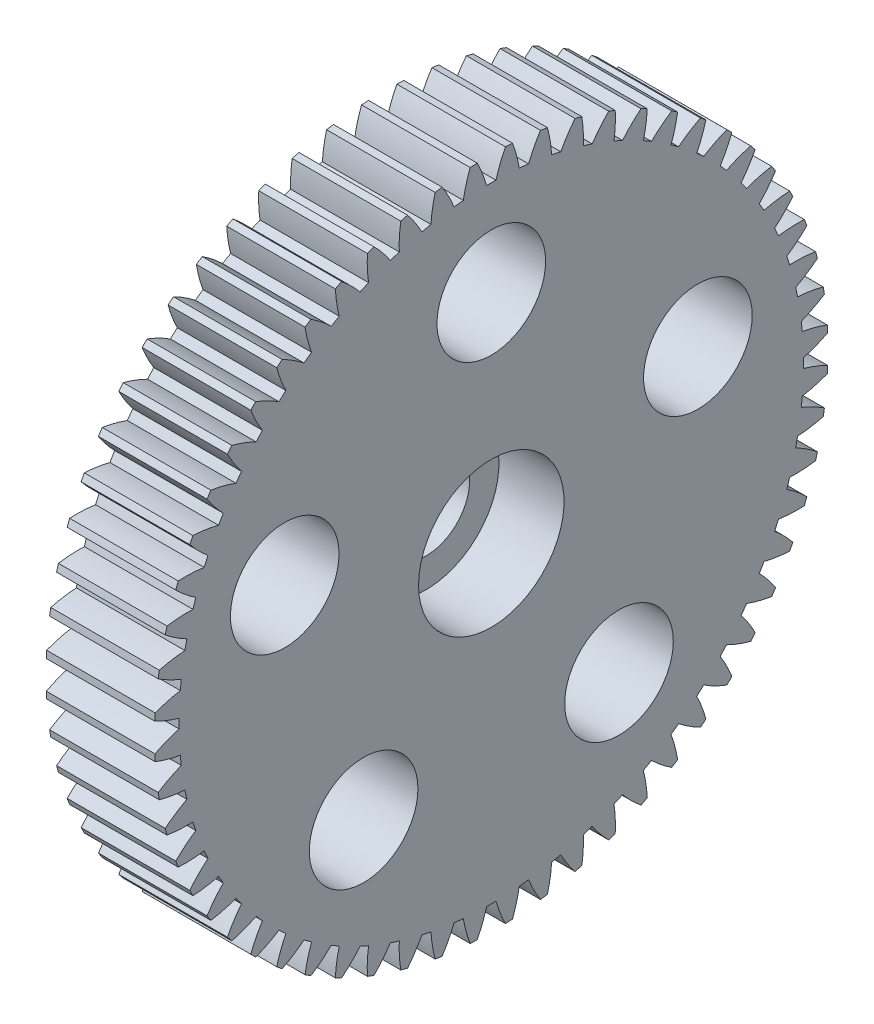
SolidWorks part; units mm, degrees
ref_plane "Plane1" through (0, 0, 0) normal (0, 0, 1) x (1, 0, 0)
ref_plane "Plane2" through (0, 0, 0) normal (0, 1, 0) x (1, 0, 0)
ref_plane "Plane3" through (0, 0, 0) normal (1, 0, 0) x (0, 0, -1)
sketch "HoldingSke" plane through (0, 0, 0) normal (0, 1, 0) x (1, 0, 0)
  line L0 (0, 0) -> (0.5, -0.866)
  line L1 (-15, 0) -> (100, 0) construction
  line L2 (0, 0) -> (-2.1039, 2.3779)
  line L3 (0, 0) -> (-11.863, 4.5341)
  line L4 (0, 0) -> (4.318, 7.479)
  line L5 (0, 0) -> (-46.8476, -17.4728)
  line L6 (0, 0) -> (-4.1448, -2.7965)
  line L7 (-2.1039, 2.3779) -> (8.6586, 51.2059)
  line L8 (-76.2, 54.61) -> (-75.7, 54.61)
  line L9 (-71.009, 38.7566) -> (-53.1078, 45.2721)
  line L10 (-76.2, 71.12) -> (104.1128, 71.12)
  line L11 (0, 0) -> (-5, 0)
  line L12 (-76.2, 101.6) -> (-76.162, 101.6)
  line L13 (24.9733, 27.94) -> (52.9518, 28.4284)
  line L14 (24.9733, 27.94) -> (24.9743, 27.94)
  line L15 (24.9733, 27.94) -> (100.4006, 29.5858)
  line L16 (-63.627, -1) -> (-12.827, -1)
  circle A0 centre (0, 0) radius 1.5
  circle A1 centre (0, 0) radius 28.749
  circle A2 centre (0, 0) radius 37.5
  circle A3 centre (0, 0) radius 1.5
  dimension "MHD" = 57.498
  dimension "Hub_dia" = 75
  dimension "Bore" = 3
  dimension "MBD" = 3
  dimension "Num_teeth" = 60
  dimension "Pitch" = 1
  dimension "Overall_len" = 50
  dimension "Show_teeth" = 60
  dimension "Thickness" = 5
  dimension "OAL" = 50.0001
  dimension "T_dim" = 0.5
  dimension "Ap" = 20
  dimension "H" = 19.05
  dimension "Pitch_radius" = 180.3128
  dimension "Width" = 5
  dimension "Backlash" = 0.038
  dimension "Addendum_fac" = 1
  dimension "Dedendum_fac" = 1.25
  dimension "Clearance_fac" = 0.25
  dimension "Dedendum_add" = 0.001
  dimension "Module" = 1
sketch "BasProSke" plane through (0, 0, 0) normal (0, 1, 0) x (1, 0, 0)
  line L0 (-10, 0) -> (60, 0) construction
  line L1 (0, 0) -> (0, 31)
  line L2 (0, 0) -> (10, 0)
  line L3 (10, 0) -> (10, 31)
  line L4 (10, 31) -> (0, 31)
  dimension "Thickness" = 10
  dimension "Diameter" = 62
revolve "Base-Revolve" add sketch "BasProSke" angle 360 about L0
sketch "TooCutSke" plane through (0, 0, 0) normal (1, 0, 0) x (0, 0, -1)
  line L1 (0, 0) -> (0, 107) construction
  line L2 (0, 0) -> (-0.8518, 29.9879) construction
  line L3 (0, 0) -> (-3.1393, 59.9006) construction
  line L4 (-0.8518, 29.9879) -> (-1.5696, 29.9503) construction
  arc A0 (0.4302, 28.7458) -> (-0.4302, 28.7458) centre (0, 0) ccw
  arc A1 (1.3127, 30.9976) -> (-1.3127, 30.9976) centre (0, 0) ccw
  circle A2 centre (0, 0) radius 30 construction
  circle A3 centre (0, 0) radius 28.1908 construction
  arc A4 (-0.4302, 28.7458) -> (-1.3127, 30.9976) centre (-11.9871, 25.5153) ccw
  arc A5 (1.3127, 30.9976) -> (0.4302, 28.7458) centre (11.9871, 25.5153) ccw
  dimension "Root_dia" = 57.498
  dimension "Overcut_dia" = 62.0508
  dimension "Pitch_dia" = 60
  dimension "Base_dia" = 56.3816
  dimension "Flank_rad" = 12
  dimension "Half_ang" = 3
  dimension "Half_CT" = 0.7188
extrude "ToothCut" cut sketch "TooCutSke" along normal through all
fillet "Breaks" [suppressed] radius 0.02
fillet "RootFillets" [suppressed] radius 0.251
pattern_circular "TeethCuts" count 60 over 360 about axis through (0, 0, 0) along (1, 0, 0) of "ToothCut", "RootFillets", "Breaks"
sketch "HubNeaOneSke" plane through (0, 0, 0) normal (-1, 0, 0) x (0, 0, 1)
  circle A0 centre (0, 0) radius 28.749
  dimension "Diameter" = 57.498
extrude "HubNearOne" [suppressed] add sketch "HubNeaOneSke" along normal blind 40.0001
sketch "HubNeaBotSke" plane through (0, 0, 0) normal (-1, 0, 0) x (0, 0, 1)
  circle A0 centre (0, 0) radius 28.749
  dimension "Diameter" = 57.498
extrude "HubNearBoth" [suppressed] add sketch "HubNeaBotSke" along normal blind 20
ref_plane "FarPln" through (10, 0, 0) normal (1, 0, 0) x (0, 0, -1)
sketch "HubFarSke" plane through (10, 0, 0) normal (1, 0, 0) x (0, 0, -1)
  circle A0 centre (0, 0) radius 28.749
  dimension "Diameter" = 57.498
extrude "HubFar" [suppressed] add sketch "HubFarSke" along normal blind 20
sketch "BorSke" plane through (0, 0, 0) normal (1, 0, 0) x (0, 0, -1)
  circle A0 centre (0, 0) radius 6.7
  dimension "Diameter" = 13.4
extrude "Bore" cut sketch "BorSke" along normal mid plane 100.0001
sketch "KeySke" plane through (0, 0, 0) normal (1, 0, 0) x (0, 0, -1)
  line L0 (-0.6, 0) -> (-0.6, 2)
  line L1 (-0.6, 2) -> (0.6, 2)
  line L2 (0.6, 2) -> (0.6, 0)
  line L3 (0, 0) -> (0, 34) construction
  line L4 (-0.6, 0) -> (0.6, 0)
  dimension "Offset" = 2
  dimension "Width" = 1.2
extrude "Keyway" [suppressed] cut sketch "KeySke" along normal mid plane 100.0001
sketch "草图1" plane through (10, 0, 0) normal (1, 0, 0) x (0, 0, -1)
  circle A0 centre (0, 20) radius 5
  circle A1 centre (0, 0) radius 6.7 construction
  circle A2 centre (19.0211, 6.1803) radius 5
  circle A3 centre (11.7557, -16.1803) radius 5
  circle A4 centre (-11.7557, -16.1803) radius 5
  circle A5 centre (-19.0211, 6.1803) radius 5
  point P14 (0, 0)
  dimension "D1" = 10
  dimension "D2" = 20
  dimension "D3" = 5
extrude "切除-拉伸2" cut sketch "草图1" against normal blind 10
sketch "草图3" plane through (0, 0, 0) normal (-1, 0, 0) x (0, 0, 1)
  circle A0 centre (0, 0) radius 6.7
  circle A1 centre (0, 0) radius 4
  circle A2 centre (0, 0) radius 6.7 construction
  dimension "D1" = 8
extrude "凸台-拉伸2" add sketch "草图3" against normal blind 4
equation "' \"Module@HoldingSke\" = 6.35"
equation "' \"Num_teeth@HoldingSke\" = 12"
equation "' \"Ap@HoldingSke\" =  20"
equation "' \"Ap@HoldingSke\" = 20"
equation "' \"Width@HoldingSke\" = 0.5 * 25.4"
equation "' \"Hub_dia@HoldingSke\"= 1 * 25.4"
equation "' \"Hub_dia@HoldingSke\" = 1 * 25.4"
equation "' \"Overall_len@HoldingSke\" = 1.0 * 25.4"
equation "' \"Bore@HoldingSke\" = 0.75 * 25.4"
equation "' \"T_dim@HoldingSke\" = 0.1 * 25.4"
equation "' \"Width@KeySke\" = 0.25 * 25.4"
equation "' \"Show_teeth@HoldingSke\" = 13"
equation "' \"Backlash@HoldingSke\" = 0.009 * 25.4"
equation "' \"Addendum_fac@HoldingSke\" = 1.0"
equation "' \"Dedendum_fac@HoldingSke\" = 1.25"
equation "' \"Dedendum_add@HoldingSke\" = 0.00005 * 25.4"
equation "' \"Clearance_fac@HoldingSke\" = 0.25"
equation "\"Pitch@HoldingSke\" = 1 / \"Module@HoldingSke\""
equation "\"Overcut_dia@TooCutSke\" = (\"Num_teeth@HoldingSke\" + 2 * \"Addendum_fac@HoldingSke\") / \"Pitch@HoldingSke\" + 0.002 * 25.4"
equation "\"Pitch_dia@TooCutSke\" = \"Num_teeth@HoldingSke\" / \"Pitch@HoldingSke\""
equation "\"Base_dia@TooCutSke\" = \"Num_teeth@HoldingSke\" / \"Pitch@HoldingSke\" * cos((\"Ap@HoldingSke\"  * 3.14159265 / 180))"
equation "\"Root_dia@TooCutSke\" = (\"Num_teeth@HoldingSke\" + 2) / \"Pitch@HoldingSke\" - 2 * (\"Addendum_fac@HoldingSke\" + \"Dedendum_fac@HoldingSke\") / \"Pitch@HoldingSke\" - \"Dedendum_add@HoldingSke\" * 2"
equation "\"Half_ang@TooCutSke\" = 180 / \"Num_teeth@HoldingSke\""
equation "\"Half_CT@TooCutSke\" = \"Num_teeth@HoldingSke\" / \"Pitch@HoldingSke\" * sin((3.14159265 / 2 / \"Num_teeth@HoldingSke\")) / 2 - 7 * \"Backlash@HoldingSke\" / 4"
equation "\"Flank_rad@TooCutSke\" = \"Num_teeth@HoldingSke\" / \"Pitch@HoldingSke\" / 5"
equation "\"Radius@RootFillets\" = \"Clearance_fac@HoldingSke\" / \"Pitch@HoldingSke\" + \"Dedendum_add@HoldingSke\""
equation "\"Break_rad@Breaks\" = 0.02 / \"Pitch@HoldingSke\""
equation "\"Thickness@HoldingSke\" = \"Width@HoldingSke\""
equation "\"OAL@HoldingSke\" = \"Thickness@HoldingSke\""
equation "\"MHD@HoldingSke\" = (\"Num_teeth@HoldingSke\" + 2) / \"Pitch@HoldingSke\" - 2 * (\"Addendum_fac@HoldingSke\" + \"Dedendum_fac@HoldingSke\")  / \"Pitch@HoldingSke\" - \"Dedendum_add@HoldingSke\" * 2"
equation "\"MBD@HoldingSke\" = (\"Num_teeth@HoldingSke\" + 2) / \"Pitch@HoldingSke\" - 2 * (\"Addendum_fac@HoldingSke\" + \"Dedendum_fac@HoldingSke\")  / \"Pitch@HoldingSke\" - \"Dedendum_add@HoldingSke\" * 2 - 0.002 * 25.4"
equation "\"MHD@HoldingSke\" = ((sgn( \"MHD@HoldingSke\" - \"Hub_dia@HoldingSke\" )-1)*( \"MHD@HoldingSke\" - \"Hub_dia@HoldingSke\" ))/-2+ \"Hub_dia@HoldingSke\""
equation "\"MBD@HoldingSke\" = ((sgn( \"MBD@HoldingSke\" - \"Bore@HoldingSke\" )-1)*( \"MBD@HoldingSke\" - \"Bore@HoldingSke\" ))/-2+ \"Bore@HoldingSke\""
equation "\"OAL@HoldingSke\" = ((sgn( \"OAL@HoldingSke\" - \"Overall_len@HoldingSke\" )+1)*( \"OAL@HoldingSke\" - \"Overall_len@HoldingSke\" ))/2 + \"Overall_len@HoldingSke\" + 0.000002 * 25.4"
equation "\"Num_teeth@TeethCuts\" = int( \"Show_teeth@HoldingSke\" ) + 1"
equation "\"Num_teeth@TeethCuts\" = ((sgn( \"Num_teeth@TeethCuts\" - \"Num_teeth@HoldingSke\" )-1)*( \"Num_teeth@TeethCuts\" - \"Num_teeth@HoldingSke\" ))/-2+ \"Num_teeth@HoldingSke\""
equation "\"Num_teeth@TeethCuts\" = ((sgn( \"Num_teeth@TeethCuts\" - 2.0)+1)*( \"Num_teeth@TeethCuts\" - 2.0))/2 +2.0"
equation "\"Angle@TeethCuts\" = 360.0 / \"Num_teeth@HoldingSke\""
equation "\"Diameter@BasProSke\" = (\"Num_teeth@HoldingSke\" + 2 * \"Addendum_fac@HoldingSke\") / \"Pitch@HoldingSke\""
equation "' \"Fillet_rad@BasProSke\" =  \"Thickness@HoldingSke\" * 0.05"
equation "' \"Fillet_rad@BasProSke\" = \"Thickness@HoldingSke\" * 0.05"
equation "\"MHD@HoldingSke\" = ((sgn( \"MHD@HoldingSke\" - \"Root_dia@TooCutSke\" )-1)*( \"MHD@HoldingSke\" - \"Root_dia@TooCutSke\" ))/-2+ \"Root_dia@TooCutSke\""
equation "\"Diameter@HubNeaOneSke\" = \"MHD@HoldingSke\""
equation "\"Length@HubNearOne\" = \"OAL@HoldingSke\" - \"Thickness@BasProSke\""
equation "\"Diameter@HubNeaBotSke\" = \"MHD@HoldingSke\""
equation "\"Length@HubNearBoth\" = ( \"OAL@HoldingSke\" - \"Thickness@BasProSke\" ) / 2.0"
equation "\"Thickness@FarPln\" = \"Thickness@BasProSke\""
equation "\"Diameter@HubFarSke\" = \"MHD@HoldingSke\""
equation "\"Length@HubFar\" = ( \"OAL@HoldingSke\" - \"Thickness@BasProSke\" ) / 2.0"
equation "\"D1@Bore\" = \"OAL@HoldingSke\" * 2.0"
equation "\"D1@Keyway\" = \"OAL@HoldingSke\" * 2.0"
equation "\"Offset@KeySke\" = \"T_dim@HoldingSke\" + \"MBD@HoldingSke\" / 2.0"
